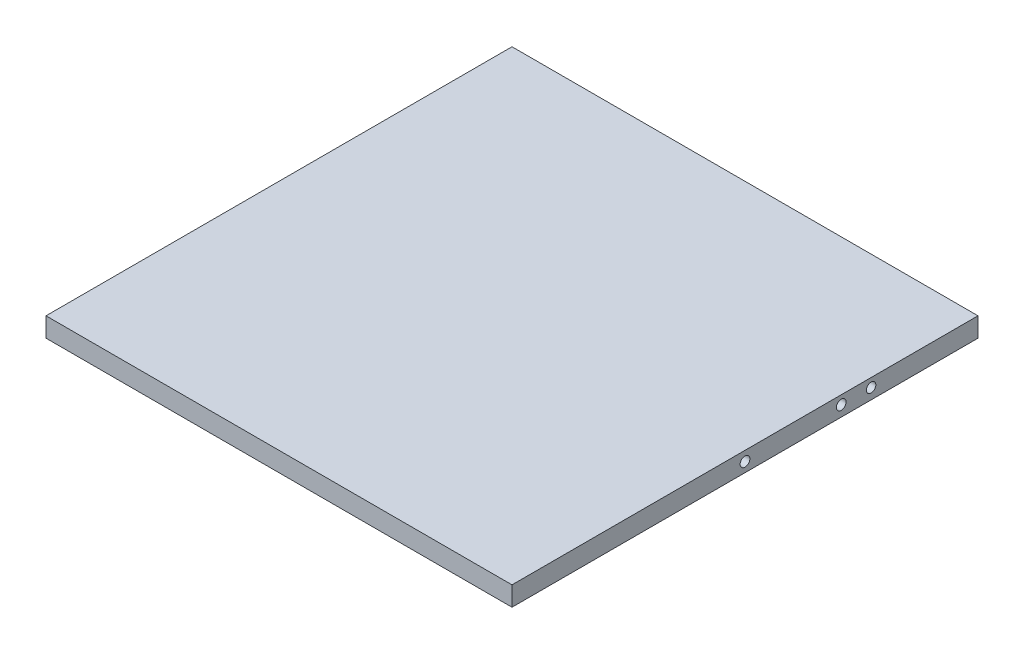
SolidWorks part; units mm, degrees
ref_plane "Front Plane" through (0, 0, 0) normal (0, 0, 1) x (1, 0, 0)
ref_plane "Top Plane" through (0, 0, 0) normal (0, 1, 0) x (1, 0, 0)
ref_plane "Right Plane" through (0, 0, 0) normal (1, 0, 0) x (0, 0, -1)
sketch "Sketch2" plane through (0, 0, 0) normal (0, 1, 0) x (1, 0, 0)
  line L1 (-250.8402, 154.9522) -> (53.9598, 154.9522)
  line L2 (-250.8402, 154.9522) -> (-250.8402, -149.8478)
  line L3 (-250.8402, -149.8478) -> (53.9598, -149.8478)
  line L4 (53.9598, 154.9522) -> (53.9598, -149.8478)
  dimension "D1" = 304.8
  dimension "D2" = 304.8
extrude "Boss-Extrude1" add sketch "Sketch2" along normal blind 12.7
sketch "Sketch3" plane through (53.9598, 0, 0) normal (1, 0, 0) x (0, 0, -1)
  circle A0 centre (2.5522, 6.35) radius 3.175
  dimension "D1" = 6.35
extrude "Cut-Extrude1" cut sketch "Sketch3" against normal through all
sketch "Sketch4" plane through (-250.8402, 0, 32.1016) normal (-1, 0, 0) x (0, 0, 1)
  circle A0 centre (-97.6075, 7.0509) radius 3.175
  dimension "D1" = 6.35
extrude "Cut-Extrude2" cut sketch "Sketch4" against normal through all
sketch "Sketch8" plane through (-250.8402, 0, 0) normal (-1, 0, 0) x (0, 0, 1)
  circle A0 centre (-85.0309, 7.0286) radius 3.0896
extrude "Cut-Extrude3" cut sketch "Sketch8" against normal through all both and the other way through all
scale "Scale1" scale about centroid uniform scaling yes scale factor 1.5
